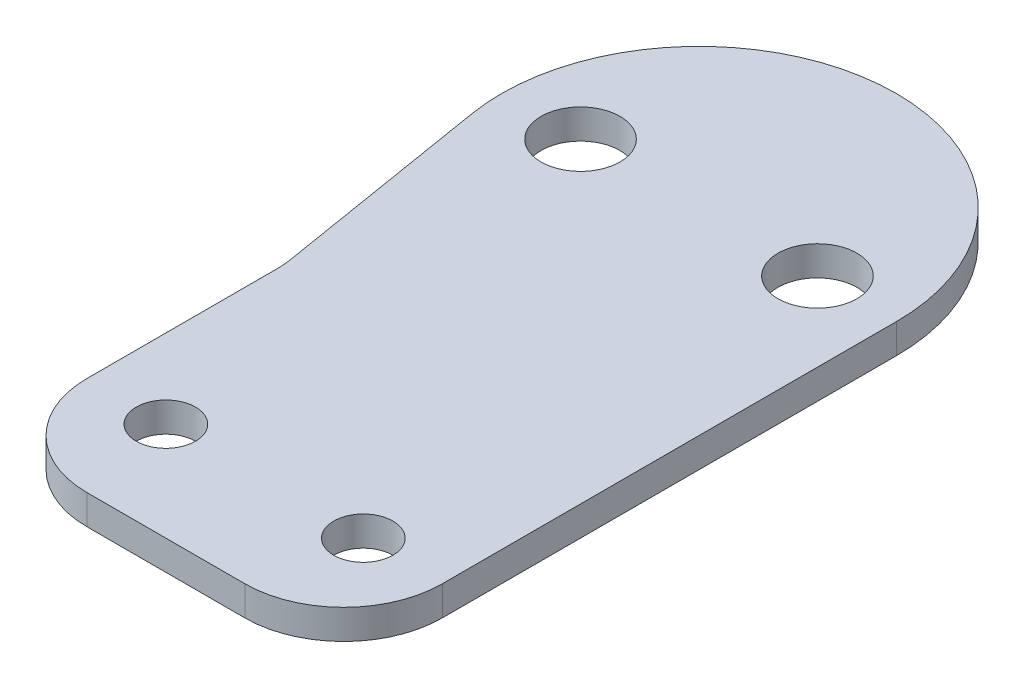
SolidWorks part; units mm, degrees
material "1060 合金"
ref_plane "正面" through (0, 0, 0) normal (0, 0, 1) x (1, 0, 0)
ref_plane "平面" through (0, 0, 0) normal (0, 1, 0) x (1, 0, 0)
ref_plane "右側面" through (0, 0, 0) normal (1, 0, 0) x (0, 0, -1)
sketch "ｽｹｯﾁ1" plane through (0, 0, 0) normal (0, 1, 0) x (1, 0, 0)
  line L0 (0, 19) -> (0, -19) construction
  line L1 (-9, -19) -> (9, -19)
  line L2 (-9, -19) -> (-9, 19)
  line L3 (-9, 19) -> (9, 19)
  line L4 (9, -19) -> (9, 19)
  line L5 (-9, -19) -> (9, 19) construction
  line L6 (-9, 19) -> (9, -19) construction
  line L7 (-9, 0) -> (9, 0) construction
  line L8 (5, 9) -> (-7, 9) construction
  line L9 (-10.868, 7.3803) -> (-9, -4)
  line L10 (-1, 19) -> (-1, -1) construction
  line L11 (-9, -4) -> (9, -4) construction
  line L12 (9, -4) -> (9, 9)
  line L13 (5, 9) -> (5, -14) construction
  line L14 (9, -19) -> (9, 9)
  circle A0 centre (-5, -14) radius 1.5
  circle A1 centre (5, -14) radius 1.5
  circle A2 centre (-7, 9) radius 2
  circle A3 centre (5, 9) radius 2
  circle A4 centre (-1, 9) radius 10
  circle A5 centre (-1, 15) radius 2 construction
  circle A6 centre (-1, 3) radius 2 construction
  circle A7 centre (-1, 9) radius 2 construction
  point P0 (0, 0)
  dimension "D1" = 10
  dimension "D3" = 5
  dimension "D4" = 3
  dimension "D5" = 23
  dimension "D7" = 12
  dimension "D8" = 20
  dimension "D10" = 4
  dimension "D11" = 12
  dimension "D2" = 4
  dimension "D9" = 15
extrude "ﾎﾞｽ - 押し出し1" add sketch "ｽｹｯﾁ1" along normal blind 1.5 contours A4 A2 A3 | A4 L9 L2 L1 L4 A0 A1 | L2 A4 | A4 L9 L2
fillet "ﾌｨﾚｯﾄ1" radius 5 3 edges at (-9, 0.75, 4) (9, 0.75, 19) (-9, 0.75, 19)
